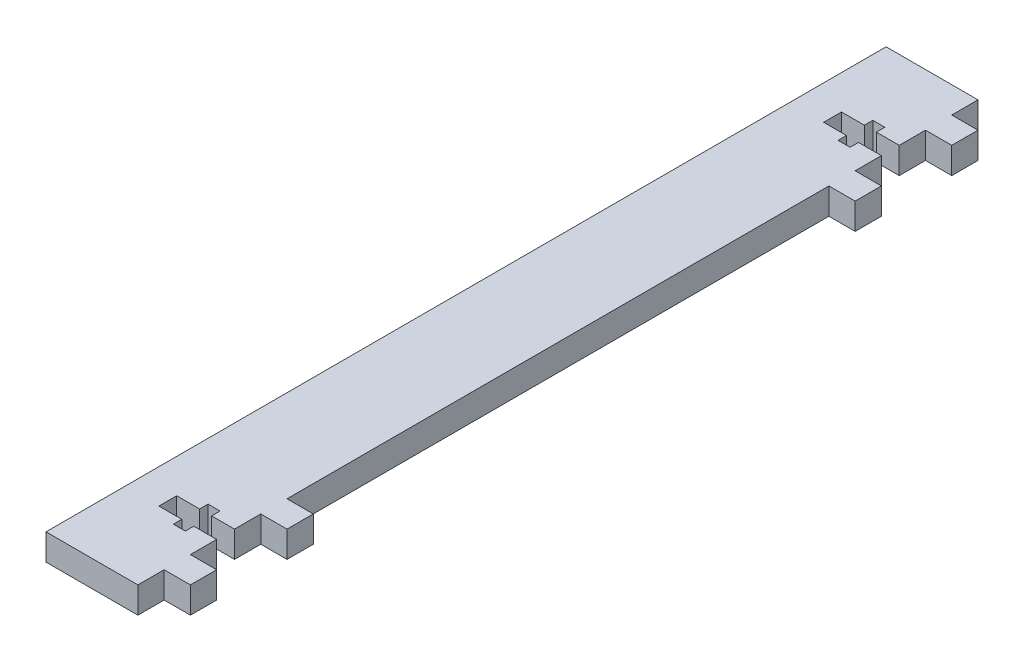
SolidWorks part; units mm, degrees
ref_plane "Front Plane" through (0, 0, 0) normal (0, 0, 1) x (1, 0, 0)
ref_plane "Top Plane" through (0, 0, 0) normal (0, 1, 0) x (1, 0, 0)
ref_plane "Right Plane" through (0, 0, 0) normal (1, 0, 0) x (0, 0, -1)
sketch "Sketch1" plane through (0, 0, 0) normal (0, 1, 0) x (1, 0, 0)
  line L0 (11.1125, 101.6) -> (11.1125, 95.25)
  line L1 (-11.1125, -101.6) -> (11.1125, -101.6)
  line L2 (-11.1125, -101.6) -> (-11.1125, 101.6)
  line L3 (-11.1125, 101.6) -> (11.1125, 101.6)
  line L4 (-11.1125, 0) -> (11.1125, 0) construction
  line L5 (-11.1125, -101.6) -> (11.1125, 101.6) construction
  line L6 (-11.1125, 101.6) -> (11.1125, -101.6) construction
  line L7 (11.1125, -95.25) -> (11.1125, -101.6)
  line L8 (11.1125, 65.532) -> (11.1125, -65.532)
  point P0 (0, 0)
  line B0 (11.1125, 71.882) -> (17.4625, 71.882)
  line B1 (17.4625, 71.882) -> (17.4625, 65.532)
  line B2 (17.4625, 65.532) -> (11.1125, 65.532)
  line B3 (11.1125, 78.232) -> (5.5775, 78.232)
  line B4 (5.5775, 78.232) -> (5.5775, 76.191)
  line B5 (5.5775, 76.191) -> (2.6775, 76.191)
  line B6 (2.6775, 76.191) -> (2.6775, 78.232)
  line B7 (2.6775, 78.232) -> (-2.8575, 78.232)
  line B8 (-2.8575, 78.232) -> (-2.8575, 82.55)
  line B9 (-2.8575, 82.55) -> (2.6775, 82.55)
  line B10 (2.6775, 82.55) -> (2.6775, 84.591)
  line B11 (2.6775, 84.591) -> (5.5775, 84.591)
  line B12 (5.5775, 84.591) -> (5.5775, 82.55)
  line B13 (5.5775, 82.55) -> (11.1125, 82.55)
  line B14 (-2.8575, 80.391) -> (11.1125, 80.391) construction
  line B15 (11.1125, 88.9) -> (11.1125, 82.55)
  line B16 (17.4625, 95.25) -> (11.1125, 95.25)
  line B17 (11.1125, 71.882) -> (11.1125, 78.232)
  line B18 (17.4625, 88.9) -> (17.4625, 95.25)
  line B19 (11.1125, 88.9) -> (17.4625, 88.9)
  line B20 (11.1125, -71.882) -> (17.4625, -71.882)
  line B21 (17.4625, -71.882) -> (17.4625, -65.532)
  line B22 (17.4625, -65.532) -> (11.1125, -65.532)
  line B23 (11.1125, -78.232) -> (5.5775, -78.232)
  line B24 (5.5775, -78.232) -> (5.5775, -76.191)
  line B25 (5.5775, -76.191) -> (2.6775, -76.191)
  line B26 (2.6775, -76.191) -> (2.6775, -78.232)
  line B27 (2.6775, -78.232) -> (-2.8575, -78.232)
  line B28 (-2.8575, -78.232) -> (-2.8575, -82.55)
  line B29 (-2.8575, -82.55) -> (2.6775, -82.55)
  line B30 (2.6775, -82.55) -> (2.6775, -84.591)
  line B31 (2.6775, -84.591) -> (5.5775, -84.591)
  line B32 (5.5775, -84.591) -> (5.5775, -82.55)
  line B33 (5.5775, -82.55) -> (11.1125, -82.55)
  line B34 (-2.8575, -80.391) -> (11.1125, -80.391) construction
  line B35 (11.1125, -88.9) -> (11.1125, -82.55)
  line B36 (17.4625, -95.25) -> (11.1125, -95.25)
  line B37 (11.1125, -71.882) -> (11.1125, -78.232)
  line B38 (17.4625, -88.9) -> (17.4625, -95.25)
  line B39 (11.1125, -88.9) -> (17.4625, -88.9)
  dimension "D1" = 203.2
  dimension "D2" = 22.225
  dimension "D3" = 6.35
sketch_block_instance "Male T-slot assembly-1"
sketch_block "Male T-slot assembly" parameters "D1"=6.35, "D2"=6.35, "D3"=4.318, "D4"=2.9, "D5"=8.4, "D6"=13.97, "D7"=6.35
sketch_block_instance "Male T-slot assembly-6"
extrude "Boss-Extrude1" add sketch "Sketch1" along normal blind 6.35 contours B39 B35 B33 B32 B31 B30 B29 B28 B27 B26 B25 B24 B23 B37 B20 B21 B22 L8 B2 B1 B0 B17 B3 B4 B5 B6 B7 B8 B9 B10 B11 B12 B13 B15 B19 B18 B16 L0 L3 L2 L1 L7 B36 B38
equation "\"Ball Diameter\"= 1.75in"
equation "\"Ball Radius\" = \"Ball Diameter\"/2"
equation "\"Sheet Thickness\"= 0.25in"
equation "\"Screw Diameter\"= .17in"
equation "\"Robot Diameter\"= 14in"
equation "\"Castor Screw Diameter\"= 0.22in"
equation "\"Wheel Diameter\" = 4in"
equation "\"Nut Diameter\" = 8.4mm"
equation "\"Nut Height\" = 2.9mm"
equation "\"Screw Height\" = 0.55in"
equation "\"Pulley Diameter\" = 1in"
equation "\"Reactor Height\" = 14in"
equation "\"Elevator Height\" = 11.5in"
equation "\"Elevator Width\" = \"Ball Diameter\" + 0.25in"
equation "\"Elevator Bearing Diameter\" = sqr(2*(\"Sheet Thickness\"^2)) + 0.2in"
equation "\"Elevator Axle Endcap Diameter\" = \"Pulley Diameter\" + 0.25in"
equation "\"Elevator Axle Length\" = \"Elevator Width\" + 8*\"Sheet Thickness\""
equation "\"Elevator Clearance from Axis\" = 3.28in"
equation "\"Elevator Horizontal Clearance\" = \"Elevator Width\" + 0.5in"
equation "\"Claw Horizontal Seperation\" = (\"Elevator Width\"/2) - (1.5 * \"Sheet Thickness\") - 0.15in"
equation "\"Claw Radius\" = \"Ball Radius\" + 0.1in"
equation "\"Castor Wheel Height\" = 1.25in"
equation "\"Length of Chute\" = 8in"
equation "\"D1@Sketch1\"=\"Length of Chute\""
equation "\"D2@Sketch1\"=\"Ball Radius\""
